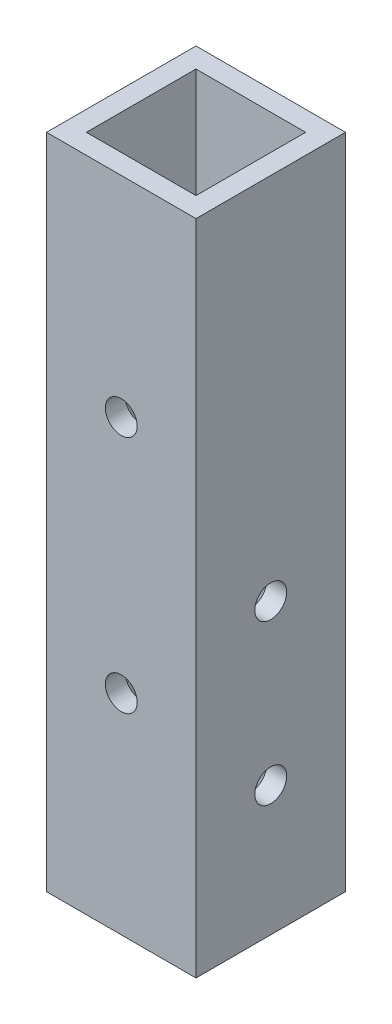
SolidWorks part; units mm, degrees
ref_plane "Front Plane" through (0, 0, 0) normal (0, 0, 1) x (1, 0, 0)
ref_plane "Top Plane" through (0, 0, 0) normal (0, 1, 0) x (1, 0, 0)
ref_plane "Right Plane" through (0, 0, 0) normal (1, 0, 0) x (0, 0, -1)
sketch "Sketch1" plane through (0, 0, 0) normal (0, 1, 0) x (1, 0, 0)
  line L0 (2, 2) -> (2, 13)
  line L1 (0, 0) -> (15, 0)
  line L2 (0, 0) -> (0, 15)
  line L3 (0, 15) -> (15, 15)
  line L4 (15, 0) -> (15, 15)
  line L5 (2, 13) -> (13, 13)
  line L6 (13, 2) -> (13, 13)
  line L7 (2, 2) -> (13, 2)
  dimension "D1" = 15
  dimension "D2" = 2
extrude "Boss-Extrude1" add sketch "Sketch1" along normal blind 66
sketch "Sketch3" plane through (0, 0, -15) normal (0, 0, -1) x (-1, 0, 0)
  line L0 (-15, 33) -> (0, 33) construction
  line L1 (-15, 66) -> (-15, 0) construction
  line L2 (0, 66) -> (0, 0) construction
  line L3 (-7.5, 66) -> (-7.5, 0) construction
  line L4 (-15, 66) -> (0, 66) construction
  line L5 (-15, 0) -> (0, 0) construction
  circle A0 centre (-7.5, 21) radius 1.6
  circle A1 centre (-7.5, 45) radius 1.6
  dimension "D1" = 3.2
  dimension "D2" = 12
  dimension "D3" = 12
extrude "Cut-Extrude1" cut sketch "Sketch3" against normal through all
sketch "Sketch4" plane through (0, 0, 0) normal (-1, 0, 0) x (0, 0, 1)
  line L2 (-15, 0) -> (0, 0) construction
  line L4 (-15, 66) -> (0, 66) construction
  line L5 (-7.5, 0) -> (-7.5, 66) construction
  circle A0 centre (-7.5, 13) radius 1.6
  circle A1 centre (-7.5, 29) radius 1.6
  point P6 (0, 0)
  point P9 (0, 0)
  dimension "D1" = 3.2
  dimension "D2" = 13
  dimension "D3" = 37
extrude "Cut-Extrude2" cut sketch "Sketch4" against normal through all
